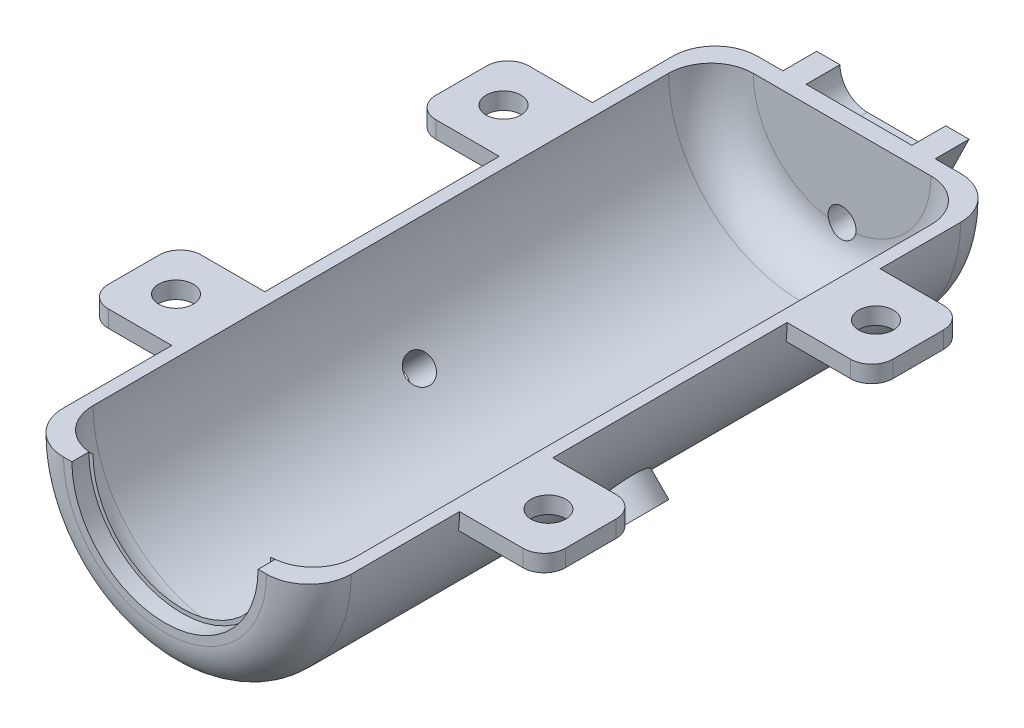
SolidWorks part; units mm, degrees
ref_plane "Front Plane" through (0, 0, 0) normal (0, 0, 1) x (1, 0, 0)
ref_plane "Top Plane" through (0, 0, 0) normal (0, 1, 0) x (1, 0, 0)
ref_plane "Right Plane" through (0, 0, 0) normal (1, 0, 0) x (0, 0, -1)
sketch "Sketch1" plane through (0, 0, 0) normal (1, 0, 0) x (0, 0, -1)
  line L0 (0, 0) -> (82, 0) construction
  line L1 (0, 12) -> (0, 11)
  line L2 (0, 11) -> (2, 11)
  line L3 (5, 17) -> (77, 17)
  line L4 (82, 12) -> (82, 0)
  line L5 (2, 11) -> (2, 10.5)
  line L6 (82, 0) -> (80, 0)
  line L7 (80, 0) -> (80, 10.5)
  line L8 (75, 15.5) -> (12, 15.5)
  line L9 (7, 15.5) -> (12, 15.5)
  arc A0 (82, 12) -> (77, 17) centre (77, 12) ccw
  arc A1 (80, 10.5) -> (75, 15.5) centre (75, 10.5) ccw
  arc A3 (5, 17) -> (0, 12) centre (5, 12) ccw
  arc A4 (7, 15.5) -> (2, 10.5) centre (7, 10.5) ccw
  dimension "D1" = 5
  dimension "D8" = 15.5
  dimension "D4" = 5
  dimension "D10" = 5
  dimension "D2" = 2
  dimension "D3" = 72
  dimension "D5" = 2
  dimension "D6" = 11
  dimension "D9" = 1.5
revolve "Revolve1" add sketch "Sketch1" angle 360 about L0
sketch "Sketch2" plane through (0, 0, 0) normal (0, 1, 0) x (1, 0, 0)
  line L0 (0, 0) -> (0, 82) construction
  line L1 (12, 82) -> (-12, 82) construction
  line L2 (-17, 41) -> (17, 41) construction
  line L3 (-17, 77) -> (-17, 5) construction
  line L4 (17, 5) -> (17, 77) construction
  circle A0 centre (0, 41) radius 2.5
  point P14 (0, 41)
  dimension "D1" = 5
sketch "Sketch4" plane through (0, 0, 0) normal (0, 1, 0) x (1, 0, 0)
  line L1 (-31.9406, 90.0974) -> (31.7505, 90.0974)
  line L2 (-31.9406, 90.0974) -> (-31.9406, -5.9147)
  line L3 (-31.9406, -5.9147) -> (31.7505, -5.9147)
  line L4 (31.7505, 90.0974) -> (31.7505, -5.9147)
extrude "Cut-Extrude3" cut sketch "Sketch4" along normal through all contours L2 L1 L4 L3
ref_plane "Plane1" through (0, 0, 0) normal (-0.7071, 0.7071, 0) x (0.7071, 0.7071, 0)
sketch "Sketch6" plane through (0, 0, 0) normal (-0.7071, 0.7071, 0) x (0.7071, 0.7071, 0)
  line L1 (-10.5, 80) -> (7.4246, 80) construction
  circle A0 centre (0, 41) radius 1.65
  dimension "D1" = 3.3
  dimension "D2" = 39
extrude "Cut-Extrude4" cut sketch "Sketch6" against normal through all both and the other way through all
ref_plane "Plane2" through (7.7782, 7.7782, 0) normal (-0.7071, -0.7071, 0) x (0, 0, 1)
sketch "Sketch7" plane through (7.7782, 7.7782, 0) normal (-0.7071, -0.7071, 0) x (0, 0, 1)
  line L1 (-80, -7.4246) -> (-80, 7.4246) construction
  circle A0 centre (-41, 0) radius 1.65
  dimension "D2" = 3.3
  dimension "D1" = 39
extrude "Cut-Extrude5" cut sketch "Sketch7" against normal through all both and the other way through all
ref_plane "Plane5" through (0, 0, -82) normal (0, 0, -1) x (-1, 0, 0)
sketch "Sketch9" plane through (0, 0, -82) normal (0, 0, -1) x (-1, 0, 0)
  line L0 (0, 0) -> (0, -17) construction
  arc A0 (-17, 0) -> (17, 0) centre (0, 0) ccw construction
  circle A1 centre (0, -10) radius 1.65
  dimension "D2" = 3.3
  dimension "D1" = 10
extrude "Cut-Extrude7" cut sketch "Sketch9" against normal blind 5
sketch "Sketch11" plane through (0, 0, 0) normal (-0.7071, 0.7071, 0) x (0.7071, 0.7071, 0)
  circle A0 centre (0, 41) radius 5
  dimension "D1" = 10
sketch "Sketch12" plane through (0, 0, 0) normal (-0.7071, 0.7071, 0) x (0.7071, 0.7071, 0)
curve "Curve1"
sketch3d "3DSketch2"
  spline S0 degree 3 poles (7.9536, -15.0247, -42.3292) (7.9536, -15.0247, -39.6708) (8.4721, -14.7683, -38.3808) (10.0445, -13.7473, -36.5474) (11.0901, -12.9511, -36.0009) (12.9469, -11.0951, -35.9991) (13.7443, -10.0492, -36.5415) (14.7723, -8.4658, -38.3886) (15.0244, -7.9541, -39.6881) (15.0249, -7.9531, -42.3076) (14.7725, -8.4653, -43.61) (13.7459, -10.0469, -45.4566) (12.9541, -11.0874, -45.9996) (11.0897, -12.9521, -46.0004) (10.0455, -13.7465, -45.4534) (8.4727, -14.768, -43.6203) (7.9536, -15.0247, -42.3292) (7.9536, -15.0247, -39.6708) (8.4721, -14.7683, -38.3808) knots -0.125 -0.125 0 0 0.125 0.125 0.25 0.25 0.375 0.375 0.5 0.5 0.625 0.625 0.75 0.75 0.875 0.875 1 1 1.125 1.125 1.25 only from (7.9536, -15.0247, -41) to (7.9536, -15.0247, -41) construction
  spline S1 degree 3 poles (7.9536, -15.0247, -42.3292) (7.9536, -15.0247, -39.6708) (8.4721, -14.7683, -38.3808) (10.0445, -13.7473, -36.5474) (11.0901, -12.9511, -36.0009) (12.9469, -11.0951, -35.9991) (13.7443, -10.0492, -36.5415) (14.7723, -8.4658, -38.3886) (15.0244, -7.9541, -39.6881) (15.0249, -7.9531, -42.3076) (14.7725, -8.4653, -43.61) (13.7459, -10.0469, -45.4566) (12.9541, -11.0874, -45.9996) (11.0897, -12.9521, -46.0004) (10.0455, -13.7465, -45.4534) (8.4727, -14.768, -43.6203) (7.9536, -15.0247, -42.3292) (7.9536, -15.0247, -39.6708) (8.4721, -14.7683, -38.3808) knots -0.125 -0.125 0 0 0.125 0.125 0.25 0.25 0.375 0.375 0.5 0.5 0.625 0.625 0.75 0.75 0.875 0.875 1 1 1.125 1.125 1.25 only from (7.9536, -15.0247, -41) to (7.9536, -15.0247, -41)
ref_plane "Plane6" through (0, 0, -41) normal (0, 0, 1) x (1, 0, 0)
sketch "Sketch13" plane through (0, 0, -41) normal (0, 0, 1) x (1, 0, 0)
  line L0 (0, 0) -> (15.8643, -15.8643) construction
  line L1 (0, 0) -> (31.1617, 0) construction
  arc A0 (10.7973, -13.1308) -> (13.1308, -10.7973) centre (0, 0) ccw construction
  arc A1 (10.7973, -13.1308) -> (13.1308, -10.7973) centre (0, 0) ccw
  dimension "D1" = 45
ref_plane "Plane7" through (0, 0, -41) normal (0, 0, 1) x (1, 0, 0)
sketch "Sketch14" plane through (0, 0, -41) normal (0, 0, 1) x (1, 0, 0)
  line L0 (11.9142, -12.1265) -> (16.1569, -16.3691) construction
  line L2 (17, 0) -> (12, 0) construction
  arc A0 (-17, 0) -> (17, 0) centre (0, 0) ccw construction
  point P7 (11.9142, -12.1265)
  dimension "D1" = 45
  dimension "D2" = 6
  dimension "D3" = 12.1265
ref_plane "Plane8" through (-11.1498, 10.7672, 0) normal (0.7193, -0.6947, 0) x (0, 0, 1)
sketch "Sketch15" plane through (-11.1498, 10.7672, 0) normal (0.7193, -0.6947, 0) x (0, 0, 1)
  circle A0 centre (-41, 0.28) radius 2.1
  circle A1 centre (-41, 0.28) radius 4.1
  dimension "D1" = 4.2
  dimension "D4" = 2
  dimension "D2" = 41
  dimension "D3" = 0.28
sketch "Sketch16" plane through (7.7782, 7.7782, 0) normal (-0.7071, -0.7071, 0) x (0, 0, 1)
  circle A0 centre (-41, 0) radius 3.65
  circle A1 centre (-41, 0) radius 1.65
  dimension "D1" = 3.3
  dimension "D2" = 2
extrude "Boss-Extrude4" add sketch "Sketch16" along normal blind 3.9 from offset 27
sketch "Sketch17" plane through (0, 0, 0) normal (-0.7071, 0.7071, 0) x (0.7071, 0.7071, 0)
  circle A0 centre (0, 41) radius 3.65
  circle A1 centre (0, 41) radius 1.65
  dimension "D1" = 3.3
  dimension "D2" = 2
extrude "Boss-Extrude6" add sketch "Sketch17" against normal blind 3.9 from offset 16 offset against normal yes
sketch "Sketch18" plane through (0, 0, -82) normal (0, 0, -1) x (-1, 0, 0)
  line L0 (0, -10) -> (-4.1, -10) construction
  line L1 (-4.8061, -8.559) -> (-9, 0)
  line L2 (12, 0) -> (-12, 0) construction
  line L3 (0, -10) -> (0, 0) construction
  line L4 (-6.25, 0) -> (-9, 0) construction
  line L5 (-9, 0) -> (-6.25, 0)
  line L6 (-3, -3.25) -> (3, -3.25)
  line L7 (4.8061, -8.559) -> (9, 0)
  line L8 (6.25, 0) -> (9, 0)
  arc A0 (-4.0087, -10.8605) -> (4.0087, -10.8605) centre (0, -10) ccw
  arc A2 (-6.25, 0) -> (-3, -3.25) centre (-3, 0) ccw
  arc A3 (6.25, 0) -> (3, -3.25) centre (3, 0) cw
  arc A4 (-4.0087, -10.8605) -> (-4.8061, -8.559) centre (-13.786, -12.9592) ccw
  arc A5 (4.8061, -8.559) -> (4.0087, -10.8605) centre (13.786, -12.9592) ccw
  circle A6 centre (0, -10) radius 1.65
  point P19 (0, -3.25)
  point P23 (4.1, -10)
  dimension "D1" = 10
  dimension "D3" = 3.25
  dimension "D4" = 6
  dimension "D5" = 10
  dimension "D6" = 10
  dimension "D7" = 3.3
  dimension "D2" = 9
extrude "Boss-Extrude7" add sketch "Sketch18" along normal blind 4
sketch "Sketch19" plane through (0, 0, -86) normal (0, 0, -1) x (-1, 0, 0)
  circle A0 centre (0, -10) radius 4.1
  circle A1 centre (0, -10) radius 2.1
sketch "Sketch20" plane through (0, 0, -86) normal (0, 0, -1) x (-1, 0, 0)
  text T0 "<b>NLE</b>" font "Century Gothic" height 3.5
extrude "Cut-Extrude8" cut sketch "Sketch20" against normal blind 0.2
ref_plane "Plane9" through (0, 0, 0) normal (0, 1, 0) x (1, 0, 0)
sketch "Sketch21" plane through (0, 0, 0) normal (0, 1, 0) x (1, 0, 0)
  line L0 (-17, 67.5) -> (-25, 67.5)
  line L1 (-17, 5) -> (-17, 77) construction
  line L2 (-27, 65.5) -> (-27, 58.5)
  line L3 (-25, 56.5) -> (-17, 56.5)
  line L4 (-22, 56.5) -> (-22, 67.5) construction
  line L5 (-27, 62) -> (-17, 62) construction
  line L6 (-12, 82) -> (-9, 82) construction
  line L7 (0, 0) -> (0, 80) construction
  line L8 (10.5, 80) -> (-10.5, 80) construction
  line L9 (-17, 41) -> (17, 41) construction
  line L10 (17, 77) -> (17, 5) construction
  line L11 (-27, 20) -> (-17, 20) construction
  line L12 (-22, 25.5) -> (-22, 14.5) construction
  line L13 (-25, 25.5) -> (-17, 25.5)
  line L14 (-27, 16.5) -> (-27, 23.5)
  line L15 (-17, 14.5) -> (-25, 14.5)
  line L16 (22, 25.5) -> (22, 14.5) construction
  line L17 (27, 20) -> (17, 20) construction
  line L18 (27, 62) -> (17, 62) construction
  line L19 (22, 56.5) -> (22, 67.5) construction
  line L20 (17, 14.5) -> (25, 14.5)
  line L21 (27, 16.5) -> (27, 23.5)
  line L22 (25, 25.5) -> (17, 25.5)
  line L23 (25, 56.5) -> (17, 56.5)
  line L24 (27, 65.5) -> (27, 58.5)
  line L25 (17, 67.5) -> (25, 67.5)
  line L26 (-17, 56.5) -> (-17, 67.5) construction
  line L27 (-17, 14.5) -> (-17, 25.5)
  line L28 (17, 14.5) -> (17, 25.5)
  line L29 (17, 67.5) -> (17, 56.5)
  line L30 (-17, 67.5) -> (-16.25, 67.5)
  line L31 (-16.25, 67.5) -> (-16.25, 56.5)
  line L32 (-16.25, 56.5) -> (-17, 56.5)
  arc A1 (-25, 56.5) -> (-27, 58.5) centre (-25, 58.5) cw
  arc A2 (-27, 65.5) -> (-25, 67.5) centre (-25, 65.5) cw
  circle A3 centre (-22, 62) radius 2.05
  circle A4 centre (-22, 20) radius 2.05
  arc A5 (-27, 16.5) -> (-25, 14.5) centre (-25, 16.5) ccw
  arc A6 (-25, 25.5) -> (-27, 23.5) centre (-25, 23.5) ccw
  arc A7 (25, 25.5) -> (27, 23.5) centre (25, 23.5) cw
  arc A8 (27, 16.5) -> (25, 14.5) centre (25, 16.5) cw
  circle A9 centre (22, 20) radius 2.05
  circle A10 centre (22, 62) radius 2.05
  arc A11 (27, 65.5) -> (25, 67.5) centre (25, 65.5) ccw
  arc A12 (25, 56.5) -> (27, 58.5) centre (25, 58.5) ccw
  point P14 (-27, 56.5)
  point P17 (-27, 67.5)
  point P43 (-27, 14.5)
  point P44 (-27, 25.5)
  point P73 (27, 25.5)
  point P74 (27, 14.5)
  point P75 (27, 67.5)
  point P76 (27, 56.5)
  dimension "D3" = 20
  dimension "D4" = 2
  dimension "D6" = 4.1
  dimension "D1" = 10
  dimension "D2" = 11
  dimension "D5" = 5
  dimension "D7" = 0.75
sketch "Sketch22" plane through (0, 0, 0) normal (0, 1, 0) x (1, 0, 0)
  line L0 (-17, 67.5) -> (-17, 56.5) construction
  line L1 (-17, 5) -> (-17, 77) construction
  line L2 (-17, 56.5) -> (-24.5, 56.5)
  line L3 (-27, 59) -> (-27, 65)
  line L4 (-27, 62) -> (-17, 62) construction
  line L5 (-12, 82) -> (-9, 82) construction
  line L6 (-17, 56.5) -> (-16.25, 56.5)
  line L7 (-16.25, 56.5) -> (-16.25, 67.5)
  line L9 (-17, 67.5) -> (-16.25, 67.5)
  line L10 (-17, 67.5) -> (-24.5, 67.5)
  arc A0 (-24.5, 56.5) -> (-27, 59) centre (-24.5, 59) cw
  circle A1 centre (-22, 62) radius 2.05
  arc A2 (-24.5, 67.5) -> (-27, 65) centre (-24.5, 65) ccw
  dimension "D4" = 2.5
  dimension "D6" = 4.1
  dimension "D1" = 20
  dimension "D2" = 5.5
  dimension "D3" = 0.75
  dimension "D5" = 10
extrude "Boss-Extrude8" add sketch "Sketch22" against normal blind 2
mirror "Mirror1" about plane through (0, 0, 0) normal (1, 0, 0) of "Boss-Extrude8"
ref_plane "Plane10" through (0, 0, -42.65) normal (0, 0, -1) x (-1, 0, 0)
mirror "Mirror2" about plane through (0, 0, -42.65) normal (0, 0, -1) of "Mirror1", "Boss-Extrude8"
equation "\"`5.66\"=5.77407"
